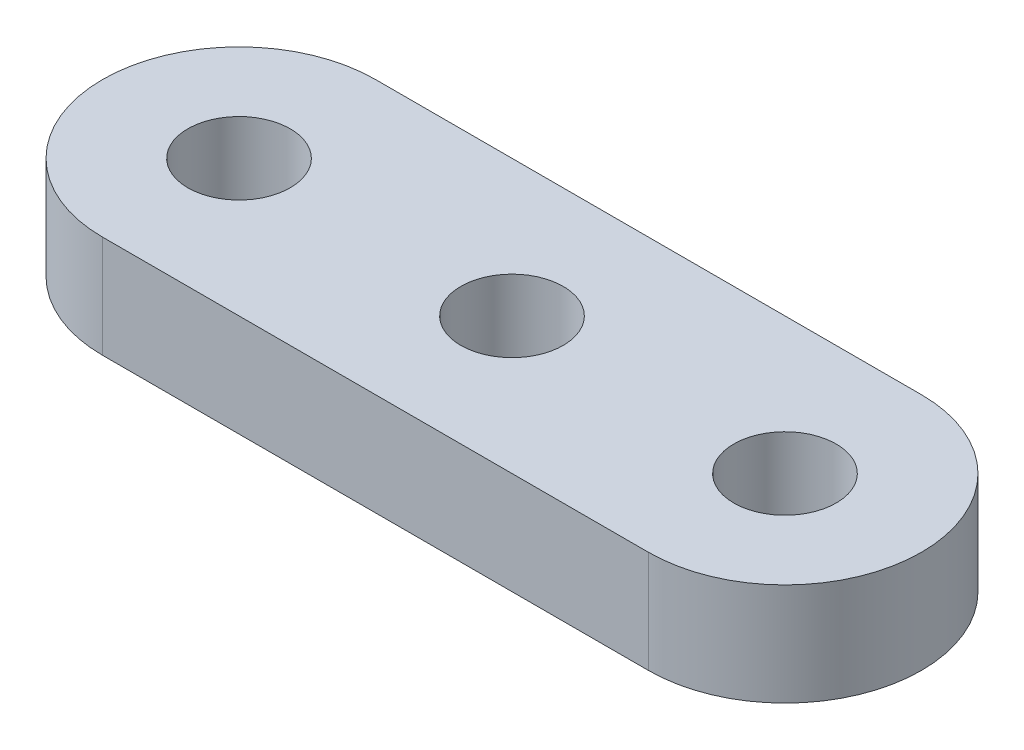
SolidWorks part; units mm, degrees
ref_plane "Front Plane" through (0, 0, 0) normal (0, 0, 1) x (1, 0, 0)
ref_plane "Top Plane" through (0, 0, 0) normal (0, 1, 0) x (1, 0, 0)
ref_plane "Right Plane" through (0, 0, 0) normal (1, 0, 0) x (0, 0, -1)
sketch "Sketch2" plane through (0, 0, 0) normal (0, 1, 0) x (1, 0, 0)
  line L0 (0, 0) -> (16, 0) construction
  line L1 (0, 4) -> (16, 4)
  line L2 (0, -4) -> (16, -4)
  arc A0 (0, 4) -> (0, -4) centre (0, 0) ccw
  arc A1 (16, -4) -> (16, 4) centre (16, 0) ccw
  circle A2 centre (0, 0) radius 1.5
  circle A3 centre (8, 0) radius 1.5
  circle A4 centre (16, 0) radius 1.5
  circle A5 centre (24, 0) radius 1.5
  circle A6 centre (32, 0) radius 1.5
  circle A7 centre (40, 0) radius 1.5
  circle A8 centre (48, 0) radius 1.5
  circle A9 centre (56, 0) radius 1.5
  circle A10 centre (64, 0) radius 1.5
  circle A11 centre (72, 0) radius 1.5
  circle A12 centre (80, 0) radius 1.5
  point P3 (8, 0)
  dimension "D1" = 3
  dimension "D2" = 8
  dimension "D3" = 16
extrude "Boss-Extrude2" add sketch "Sketch2" along normal blind 3
sketch "Sketch3" plane through (0, 0, 0) normal (0, -1, 0) x (1, 0, 0)
  line L1 (21.8589, -4.9248) -> (86.5449, -4.9248)
  line L2 (21.8589, -4.9248) -> (21.8589, 3.4218)
  line L3 (21.8589, 3.4218) -> (86.5449, 3.4218)
  line L4 (86.5449, -4.9248) -> (86.5449, 3.4218)
extrude "Cut-Extrude1" cut sketch "Sketch3" against normal blind 10
